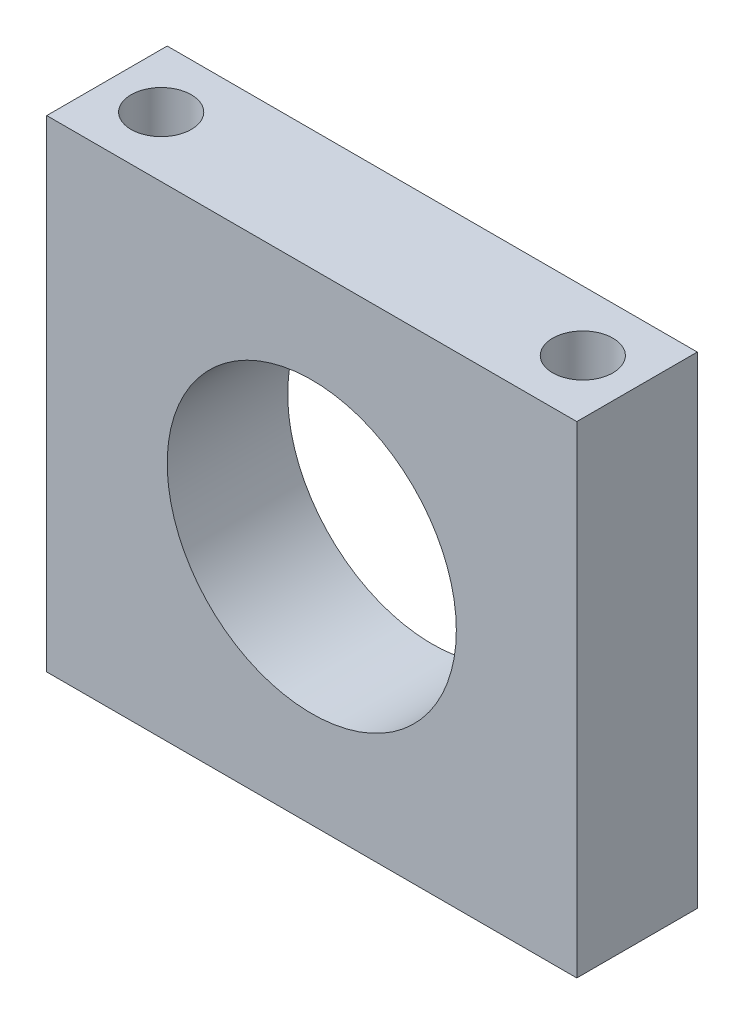
SolidWorks part; units mm, degrees
material "6063-T6"
ref_plane "Front Plane" through (0, 0, 0) normal (0, 0, 1) x (1, 0, 0)
ref_plane "Top Plane" through (0, 0, 0) normal (0, 1, 0) x (1, 0, 0)
ref_plane "Right Plane" through (0, 0, 0) normal (1, 0, 0) x (0, 0, -1)
sketch "Sketch1" plane through (0, 0, 0) normal (0, 0, 1) x (1, 0, 0)
  line L0 (11, 20) -> (11, -49980) construction
  line L1 (0, 0) -> (22, 0)
  line L2 (0, 0) -> (0, 20)
  line L3 (0, 20) -> (22, 20)
  line L4 (22, 0) -> (22, 20)
  line L5 (0, 10) -> (50000, 10) construction
  line L6 (5, 10) -> (0, 10)
  line L7 (17, 10) -> (22, 10)
  circle A0 centre (11, 10) radius 6
  point P7 (11, 20)
  point P10 (0, 10)
  dimension "D1" = 20
  dimension "D2" = 22
extrude "Boss-Extrude1" add sketch "Sketch1" along direction (0, 0, 1) on the side of the normal blind 5 contours A0 L7 L4 L3 L2 L6 | A0 L6 L2 L1 L4 L7
sketch "Sketch11" plane through (0, 20, 0) normal (0, 1, 0) x (1, 0, 0)
  line L0 (0, -2.5) -> (50000, -2.5) construction
  line L1 (0, -5) -> (0, 0) construction
  line L2 (11, -5) -> (11, 49995) construction
  line L3 (0, -5) -> (22, -5) construction
  circle A0 centre (2.25, -2.5) radius 1.25
  circle A1 centre (19.75, -2.5) radius 1.25
  point P4 (0, -2.5)
  point P9 (11, -5)
  dimension "D1" = 8.75
extrude "Cut-Extrude1" cut sketch "Sketch11" against normal through all contours A0 | A1
